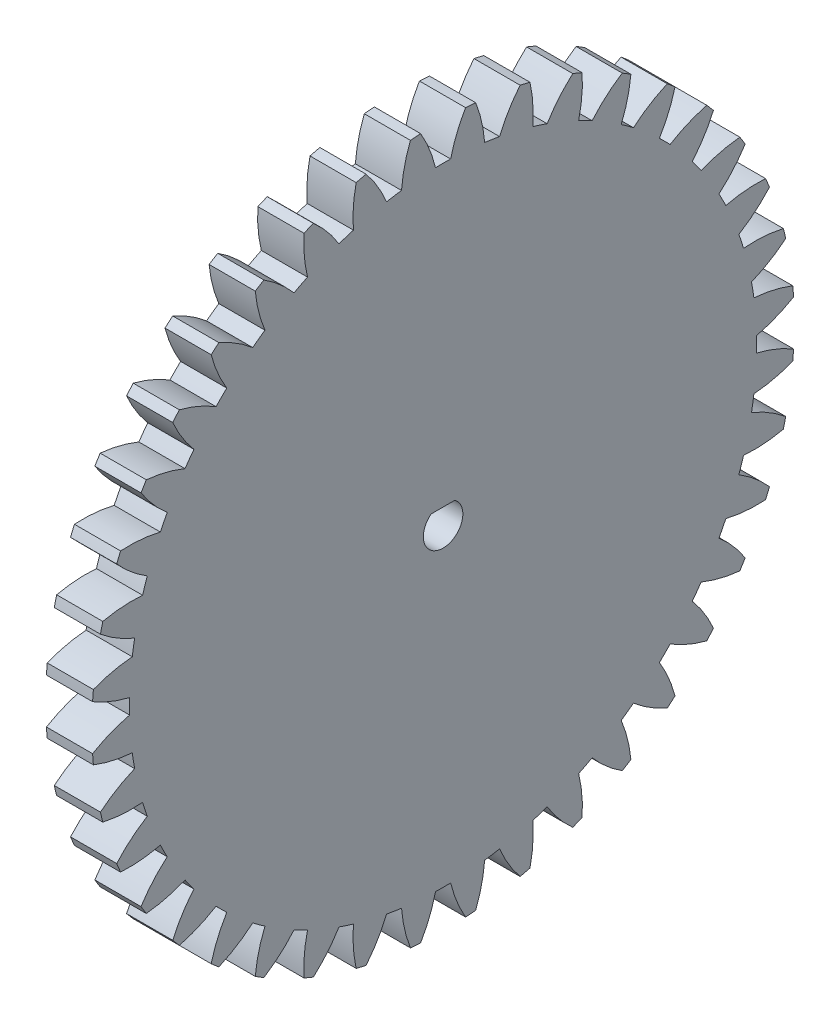
SolidWorks part; units mm, degrees
ref_plane "Plane1" through (0, 0, 0) normal (0, 0, 1) x (1, 0, 0)
ref_plane "Plane2" through (0, 0, 0) normal (0, 1, 0) x (1, 0, 0)
ref_plane "Plane3" through (0, 0, 0) normal (1, 0, 0) x (0, 0, -1)
sketch "HoldingSke" plane through (0, 0, 0) normal (0, 1, 0) x (1, 0, 0)
  line L0 (0, 0) -> (233.4903, -195.9217)
  line L1 (-15, 0) -> (100, 0) construction
  line L2 (0, 0) -> (-2.1039, 2.3779)
  line L3 (0, 0) -> (-11.863, 4.5341)
  line L4 (0, 0) -> (6.6156, 5.5511)
  line L5 (0, 0) -> (-47.5972, -17.7524)
  line L6 (0, 0) -> (-4.8428, -3.2675)
  line L7 (-2.1039, 2.3779) -> (8.8308, 51.9871)
  line L8 (-76.2, 54.61) -> (-71.1708, 54.61)
  line L9 (-71.009, 38.7566) -> (-53.1078, 45.2721)
  line L10 (-76.2, 71.12) -> (104.1128, 71.12)
  line L11 (0, 0) -> (-5.842, 0)
  line L12 (-76.2, 101.6) -> (-76.1147, 101.6)
  line L13 (24.9733, 27.94) -> (52.9518, 28.4284)
  line L14 (24.9733, 27.94) -> (24.9746, 27.94)
  line L15 (24.9733, 27.94) -> (100.4006, 29.5858)
  circle A0 centre (0, 0) radius 2.3813
  circle A1 centre (0, 0) radius 38.1
  circle A2 centre (0, 0) radius 38.1
  circle A3 centre (0, 0) radius 2.3813
  dimension "MHD" = 76.2
  dimension "Hub_dia" = 76.2
  dimension "Bore" = 4.7625
  dimension "MBD" = 4.7625
  dimension "Num_teeth" = 40
  dimension "Pitch" = 304.8
  dimension "Overall_len" = 50.8
  dimension "Show_teeth" = 40
  dimension "Thickness" = 5.842
  dimension "OAL" = 50.8001
  dimension "T_dim" = 5.0292
  dimension "Ap" = 20
  dimension "H" = 19.05
  dimension "Pitch_radius" = 180.3128
  dimension "Width" = 5.842
  dimension "Backlash" = 0.0853
  dimension "Addendum_fac" = 1
  dimension "Dedendum_fac" = 1.25
  dimension "Clearance_fac" = 0.25
  dimension "Dedendum_add" = 0.0013
sketch "BasProSke" plane through (0, 0, 0) normal (0, 1, 0) x (1, 0, 0)
  line L0 (-10, 0) -> (60, 0) construction
  line L1 (0, 0) -> (0, 44.45)
  line L2 (0, 0) -> (5.842, 0)
  line L3 (5.842, 0) -> (5.842, 44.45)
  line L4 (5.842, 44.45) -> (0, 44.45)
  dimension "Thickness" = 5.842
  dimension "Diameter" = 88.9
revolve "Base-Revolve" add sketch "BasProSke" angle 360 about L0
sketch "TooCutSke" plane through (0, 0, 0) normal (1, 0, 0) x (0, 0, -1)
  line L1 (0, 0) -> (0, 107) construction
  line L2 (0, 0) -> (-1.8113, 42.2946) construction
  line L3 (0, 0) -> (-6.6386, 84.3518) construction
  line L4 (-1.8113, 42.2946) -> (-3.3193, 42.1759) construction
  arc A0 (0.958, 39.6747) -> (-0.958, 39.6747) centre (0, 0) ccw
  arc A1 (2.8603, 44.3833) -> (-2.8603, 44.3833) centre (0, 0) ccw
  circle A2 centre (0, 0) radius 42.3333 construction
  circle A3 centre (0, 0) radius 39.7803 construction
  arc A4 (-0.958, 39.6747) -> (-2.8603, 44.3833) centre (-17.432, 35.7575) ccw
  arc A5 (2.8603, 44.3833) -> (0.958, 39.6747) centre (17.432, 35.7575) ccw
  dimension "Root_dia" = 79.3725
  dimension "Overcut_dia" = 88.9508
  dimension "Pitch_dia" = 84.6667
  dimension "Base_dia" = 79.5606
  dimension "Flank_rad" = 16.9333
  dimension "Half_ang" = 4.5
  dimension "Half_CT" = 1.5126
extrude "ToothCut" cut sketch "TooCutSke" along normal through all
fillet "Breaks" [suppressed] radius 0.0423
fillet "RootFillets" [suppressed] radius 0.5304
pattern_circular "TeethCuts" count 40 every 9 about axis through (-10, 0, 0) along (1, 0, 0) of "ToothCut", "RootFillets", "Breaks"
sketch "HubNeaOneSke" plane through (0, 0, 0) normal (-1, 0, 0) x (0, 0, 1)
  circle A0 centre (0, 0) radius 38.1
  dimension "Diameter" = 76.2
extrude "HubNearOne" [suppressed] add sketch "HubNeaOneSke" along normal blind 44.9581
sketch "HubNeaBotSke" plane through (0, 0, 0) normal (-1, 0, 0) x (0, 0, 1)
  circle A0 centre (0, 0) radius 38.1
  dimension "Diameter" = 76.2
extrude "HubNearBoth" [suppressed] add sketch "HubNeaBotSke" along normal blind 22.479
ref_plane "FarPln" through (5.842, 0, 0) normal (1, 0, 0) x (0, 0, -1)
sketch "HubFarSke" plane through (5.842, 0, 0) normal (1, 0, 0) x (0, 0, -1)
  circle A0 centre (0, 0) radius 38.1
  dimension "Diameter" = 76.2
extrude "HubFar" [suppressed] add sketch "HubFarSke" along normal blind 22.479
sketch "BorSke" plane through (0, 0, 0) normal (1, 0, 0) x (0, 0, -1)
  circle A0 centre (0, 0) radius 2.3813
  dimension "Diameter" = 4.7625
extrude "Bore" cut sketch "BorSke" along normal mid plane 101.6001
sketch "KeySke" plane through (0, 0, 0) normal (1, 0, 0) x (0, 0, -1)
  line L0 (-0.127, 0) -> (-0.127, 2.648)
  line L1 (-0.127, 2.648) -> (0.127, 2.648)
  line L2 (0.127, 2.648) -> (0.127, 0)
  line L3 (0, 0) -> (0, 34) construction
  line L4 (-0.127, 0) -> (0.127, 0)
  dimension "Offset" = 2.648
  dimension "Width" = 0.254
extrude "Keyway" [suppressed] cut sketch "KeySke" along normal mid plane 101.6001
pattern_circular "Keyway2" [suppressed] count 2 every 90 about axis through (-10, 0, 0) along (1, 0, 0)
sketch "Sketch1" plane through (5.842, 0, 0) normal (1, 0, 0) x (0, 0, -1)
  line L0 (-2.0143, 1.27) -> (2.0143, 1.27)
  line L1 (-2.0143, -1.27) -> (2.0143, -1.27)
  line L2 (0, 1.27) -> (0, -1.27) construction
  circle A0 centre (0, 0) radius 2.3813 construction
  arc A1 (-2.0143, -1.27) -> (2.0143, -1.27) centre (0, 0) ccw
  arc A2 (2.0143, 1.27) -> (-2.0143, 1.27) centre (0, 0) ccw
  point P11 (0, 0)
  dimension "D1" = 2.54
extrude "Boss-Extrude1" add sketch "Sketch1" against normal up to surface (5.842 mm away) up to face at (0, 0, -2.3813)
sketch "Sketch2" plane through (0, 0, 0) normal (-1, 0, 0) x (0, 0, 1)
  circle A0 centre (0, 0) radius 2.5
  dimension "D1" = 5
extrude "Cut-Extrude1" cut sketch "Sketch2" against normal through all
sketch "Sketch3" plane through (0, 0, 0) normal (-1, 0, 0) x (0, 0, 1)
  line L0 (-1.5, 2) -> (1.5, 2)
  arc A0 (1.5, 2) -> (-1.5, 2) centre (0, 0) ccw
  point P5 (0, -2.5)
  dimension "D1" = 5
  dimension "D2" = 4.5
extrude "Boss-Extrude2" add sketch "Sketch3" against normal up to surface (5.842 mm away) up to face at (5.842, 0, 2.5)
equation "' \"Pitch@HoldingSke\" = 4"
equation "' \"Num_teeth@HoldingSke\" = 12"
equation "' \"Ap@HoldingSke\" =  20"
equation "' \"Ap@HoldingSke\" = 20"
equation "' \"Width@HoldingSke\" = 0.5"
equation "' \"Hub_dia@HoldingSke\"= 1"
equation "' \"Hub_dia@HoldingSke\" = 1"
equation "' \"Overall_len@HoldingSke\" = 1.0"
equation "' \"Bore@HoldingSke\" = 0.75"
equation "' \"T_dim@HoldingSke\" = 0.85"
equation "' \"Width@KeySke\" = 0.25"
equation "' \"Show_teeth@HoldingSke\" = 13"
equation "' \"Backlash@HoldingSke\" = 0.009"
equation "' \"Addendum_fac@HoldingSke\" = 1.0"
equation "' \"Dedendum_fac@HoldingSke\" = 1.25"
equation "' \"Dedendum_add@HoldingSke\" = 0.00005"
equation "' \"Clearance_fac@HoldingSke\" = 0.25"
equation "' \"Pitch@HoldingSke\" = 0.5"
equation "' \"Num_teeth@HoldingSke\" = 23"
equation "' \"Show_teeth@HoldingSke\" = 23"
equation "' \"Backlash@HoldingSke\" = 0.0375"
equation "\"Overcut_dia@TooCutSke\" = (\"Num_teeth@HoldingSke\" + 2 * \"Addendum_fac@HoldingSke\") / \"Pitch@HoldingSke\" + 0.002"
equation "\"Pitch_dia@TooCutSke\" = \"Num_teeth@HoldingSke\" / \"Pitch@HoldingSke\""
equation "\"Base_dia@TooCutSke\" = \"Num_teeth@HoldingSke\" / \"Pitch@HoldingSke\" * cos((\"Ap@HoldingSke\"  * 3.14159265 / 180))"
equation "\"Root_dia@TooCutSke\" = (\"Num_teeth@HoldingSke\" + 2) / \"Pitch@HoldingSke\" - 2 * (\"Addendum_fac@HoldingSke\" + \"Dedendum_fac@HoldingSke\") / \"Pitch@HoldingSke\" - \"Dedendum_add@HoldingSke\" * 2"
equation "\"Half_ang@TooCutSke\" = 180 / \"Num_teeth@HoldingSke\""
equation "\"Half_CT@TooCutSke\" = \"Num_teeth@HoldingSke\" / \"Pitch@HoldingSke\" * sin((3.14159265 / 2 / \"Num_teeth@HoldingSke\")) / 2 - 7 * \"Backlash@HoldingSke\" / 4"
equation "\"Flank_rad@TooCutSke\" = \"Num_teeth@HoldingSke\" / \"Pitch@HoldingSke\" / 5"
equation "\"Radius@RootFillets\" = \"Clearance_fac@HoldingSke\" / \"Pitch@HoldingSke\" + \"Dedendum_add@HoldingSke\""
equation "\"Break_rad@Breaks\" = 0.02 / \"Pitch@HoldingSke\""
equation "\"Thickness@HoldingSke\" = \"Width@HoldingSke\""
equation "\"OAL@HoldingSke\" = \"Thickness@HoldingSke\""
equation "\"MHD@HoldingSke\" = (\"Num_teeth@HoldingSke\" + 2) / \"Pitch@HoldingSke\" - 2 * (\"Addendum_fac@HoldingSke\" + \"Dedendum_fac@HoldingSke\")  / \"Pitch@HoldingSke\" - \"Dedendum_add@HoldingSke\" * 2"
equation "\"MBD@HoldingSke\" = (\"Num_teeth@HoldingSke\" + 2) / \"Pitch@HoldingSke\" - 2 * (\"Addendum_fac@HoldingSke\" + \"Dedendum_fac@HoldingSke\")  / \"Pitch@HoldingSke\" - \"Dedendum_add@HoldingSke\" * 2 - 0.002"
equation "\"MHD@HoldingSke\" = ((sgn( \"MHD@HoldingSke\" - \"Hub_dia@HoldingSke\" )-1)*( \"MHD@HoldingSke\" - \"Hub_dia@HoldingSke\" ))/-2+ \"Hub_dia@HoldingSke\""
equation "\"MBD@HoldingSke\" = ((sgn( \"MBD@HoldingSke\" - \"Bore@HoldingSke\" )-1)*( \"MBD@HoldingSke\" - \"Bore@HoldingSke\" ))/-2+ \"Bore@HoldingSke\""
equation "\"OAL@HoldingSke\" = ((sgn( \"OAL@HoldingSke\" - \"Overall_len@HoldingSke\" )+1)*( \"OAL@HoldingSke\" - \"Overall_len@HoldingSke\" ))/2 + \"Overall_len@HoldingSke\" + 0.000002"
equation "\"Num_teeth@TeethCuts\" = int( \"Show_teeth@HoldingSke\" ) + 1"
equation "\"Num_teeth@TeethCuts\" = ((sgn( \"Num_teeth@TeethCuts\" - \"Num_teeth@HoldingSke\" )-1)*( \"Num_teeth@TeethCuts\" - \"Num_teeth@HoldingSke\" ))/-2+ \"Num_teeth@HoldingSke\""
equation "\"Num_teeth@TeethCuts\" = ((sgn( \"Num_teeth@TeethCuts\" - 2.0)+1)*( \"Num_teeth@TeethCuts\" - 2.0))/2 +2.0"
equation "\"Angle@TeethCuts\" = 360.0 / \"Num_teeth@HoldingSke\""
equation "\"Diameter@BasProSke\" = (\"Num_teeth@HoldingSke\" + 2 * \"Addendum_fac@HoldingSke\") / \"Pitch@HoldingSke\""
equation "\"Thickness@BasProSke\"  = \"Thickness@HoldingSke\""
equation "' \"Fillet_rad@BasProSke\" =  \"Thickness@HoldingSke\" * 0.05"
equation "' \"Fillet_rad@BasProSke\" = \"Thickness@HoldingSke\" * 0.05"
equation "\"MHD@HoldingSke\" = ((sgn( \"MHD@HoldingSke\" - \"Root_dia@TooCutSke\" )-1)*( \"MHD@HoldingSke\" - \"Root_dia@TooCutSke\" ))/-2+ \"Root_dia@TooCutSke\""
equation "\"Diameter@HubNeaOneSke\" = \"MHD@HoldingSke\""
equation "\"Length@HubNearOne\" = \"OAL@HoldingSke\" - \"Thickness@BasProSke\""
equation "\"Diameter@HubNeaBotSke\" = \"MHD@HoldingSke\""
equation "\"Length@HubNearBoth\" = ( \"OAL@HoldingSke\" - \"Thickness@BasProSke\" ) / 2.0"
equation "\"Thickness@FarPln\" = \"Thickness@BasProSke\""
equation "\"Diameter@HubFarSke\" = \"MHD@HoldingSke\""
equation "\"Length@HubFar\" = ( \"OAL@HoldingSke\" - \"Thickness@BasProSke\" ) / 2.0"
equation "\"Diameter@BorSke\" = \"MBD@HoldingSke\""
equation "\"D1@Bore\" = \"OAL@HoldingSke\" * 2.0"
equation "\"D1@Keyway\" = \"OAL@HoldingSke\" * 2.0"
equation "\"Offset@KeySke\" = \"T_dim@HoldingSke\" - \"MBD@HoldingSke\" / 2.0"
